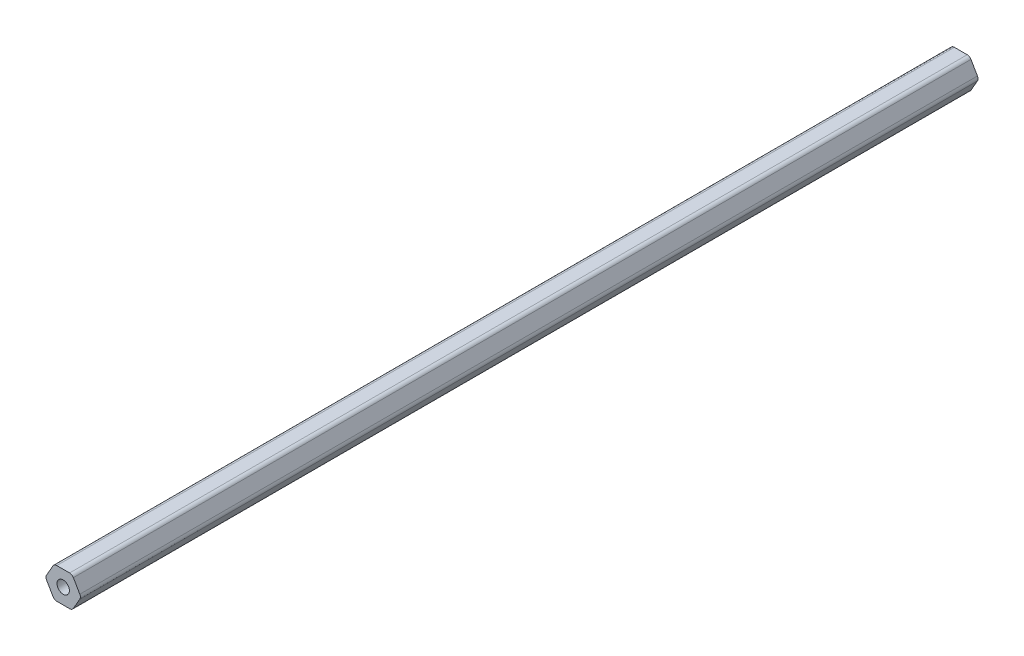
SolidWorks part; units mm, degrees
ref_plane "Front Plane" through (0, 0, 0) normal (0, 0, 1) x (1, 0, 0)
ref_plane "Top Plane" through (0, 0, 0) normal (0, 1, 0) x (1, 0, 0)
ref_plane "Right Plane" through (0, 0, 0) normal (1, 0, 0) x (0, 0, -1)
sketch "Sketch1" plane through (0, 0, 0) normal (0, 0, 1) x (1, 0, 0)
  line L1 (5.605, 0.3701) -> (1.9388, 6.7201)
  line L2 (1.9388, 6.7201) -> (-5.3935, 6.7201)
  line L3 (-5.3935, 6.7201) -> (-9.0597, 0.3701)
  line L4 (-9.0597, 0.3701) -> (-5.3935, -5.9799)
  line L5 (-5.3935, -5.9799) -> (1.9388, -5.9799)
  line L6 (1.9388, -5.9799) -> (5.605, 0.3701)
  circle A0 centre (-1.7273, 0.3701) radius 6.35 construction
  circle A1 centre (-1.7273, 0.3701) radius 2.54
  dimension "D1" = 12.7
extrude "Boss-Extrude1" add sketch "Sketch1" along normal blind 368.3
fillet "Fillet1" radius 1.778 6 edges at (-5.3935, -5.9799, 184.15) (1.9388, -5.9799, 184.15) (5.605, 0.3701, 184.15) (1.9388, 6.7201, 184.15) (-5.3935, 6.7201, 184.15) (-9.0597, 0.3701, 184.15)
